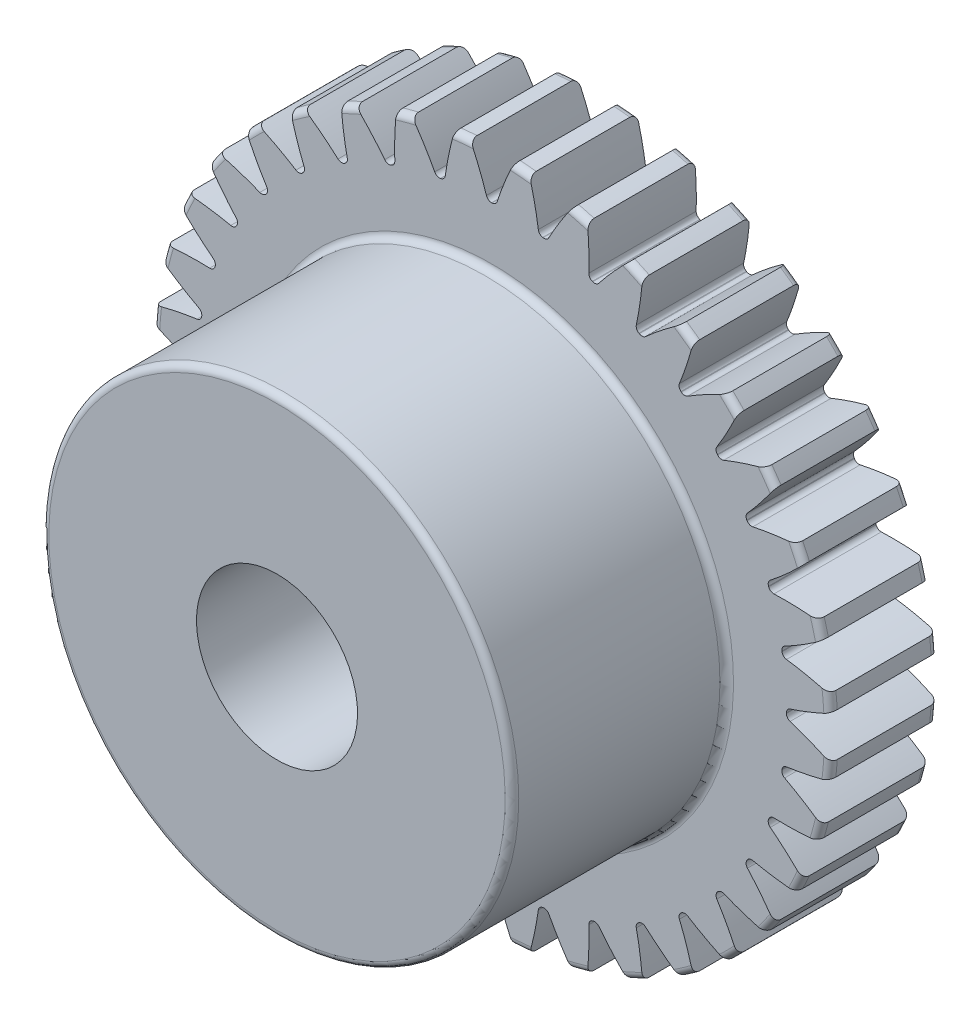
SolidWorks part; units mm, degrees
ref_plane "Front Plane" through (0, 0, 0) normal (0, 0, 1) x (1, 0, 0)
ref_plane "Top Plane" through (0, 0, 0) normal (0, 1, 0) x (1, 0, 0)
ref_plane "Right Plane" through (0, 0, 0) normal (1, 0, 0) x (0, 0, -1)
sketch "Sketch1" plane through (0, 0, 0) normal (0, 0, 1) x (1, 0, 0)
  line L0 (-457.2, 0) -> (457.2, 0) construction
  circle A0 centre (0, 0) radius 10.033 construction
  circle A1 centre (0, 0) radius 9.525 construction
  circle A2 centre (0, 0) radius 8.7101 construction
  circle A3 centre (0, 0) radius 6.9469 construction
  circle A4 centre (0, 0) radius 2.3813 construction
  dimension "D2" = 0.508
  dimension "D3" = 1.3229
  dimension "D1" = 1.3229
sketch "Sketch2" plane through (0, 0, 0) normal (1, 0, 0) x (0, 0, -1)
  line L0 (0, 0) -> (-3.175, 0) construction
  line L1 (-3.175, 0) -> (-9.525, 0) construction
  dimension "Overall Width" = 9.525
  dimension "Face Width" = 3.175
sketch "Sketch4" plane through (0, 0, 0) normal (1, 0, 0) x (0, 0, -1)
  line L0 (-9.525, 2.3813) -> (-9.525, 6.9469)
  line L1 (-9.525, 6.9469) -> (-3.175, 6.9469)
  line L2 (-3.175, 6.9469) -> (-3.175, 10.033)
  line L3 (-3.175, 10.033) -> (0, 10.033)
  line L4 (0, 10.033) -> (0, 2.3813)
  line L5 (-3.175, 6.9469) -> (-3.175, 0) construction
  line L6 (0, 10.033) -> (0, -10.033) construction
  line L7 (-3.175, 6.9469) -> (0, 6.9469) construction
  line L12 (-9.525, 2.3813) -> (0, 2.3813)
revolve "Revolve1" add sketch "Sketch4" angle 360 about L1
fillet "Fillet2" radius 0.2007 4 edges at (0, 6.9469, 9.525) (0, 6.9469, 3.175) (0, 10.033, 3.175) (0, 10.033, 0)
sketch "Sketch7" plane through (0, 0, 3.175) normal (0, 0, 1) x (1, 0, 0)
  line L0 (0, 0) -> (0, 10.033) construction
  line L1 (0.4155, 9.5159) -> (0.6217, 10.0137) construction
  line L3 (0.8744, 9.9948) -> (0.8302, 9.4888) construction
  line L4 (0.8302, 9.4888) -> (0.7591, 8.6769) construction
  line L5 (0, 0) -> (0.7591, 8.6769) construction
  line L6 (0.4155, 9.5159) -> (0, 0) construction
  line L7 (0.4155, 9.5159) -> (0.4376, 10.0235) construction
  line L8 (0.4155, 9.5159) -> (0, 0) construction
  circle A0 centre (0, 0) radius 10.033 construction
  arc A1 (-0.0073, 8.7101) -> (0.0073, 8.7101) centre (0, 0) cw
  circle A2 centre (0, 0) radius 8.7101 construction
  arc A3 (-0.4155, 9.5159) -> (0.4155, 9.5159) centre (0, 0) cw construction
  circle A4 centre (0, 0) radius 9.525 construction
  arc A5 (1.1103, 9.9714) -> (0.6381, 10.0127) centre (0, 0) ccw construction
  arc A6 (0.4155, 9.5159) -> (1.2433, 9.4435) centre (0, 0) cw construction
  arc A7 (-0.6381, 10.0127) -> (0.6381, 10.0127) centre (0, 0) cw
  arc A8 (0.1584, 8.8197) -> (0.6381, 10.0127) centre (9.2154, 5.8709) cw
  arc A9 (-0.1584, 8.8197) -> (-0.6381, 10.0127) centre (-9.2154, 5.8709) ccw
  arc A10 (-0.0073, 8.7101) -> (-0.1584, 8.8197) centre (-0.0074, 8.8688) cw
  arc A11 (0.0073, 8.7101) -> (0.1584, 8.8197) centre (0.0074, 8.8688) ccw
  point P26 (-0.1232, 8.7092)
  point P29 (0.1232, 8.7092)
  dimension "D4" = 0.1588
  dimension "D5" = 9.525
  dimension "D3" = 20
  dimension "D1" = 1.6624
  dimension "D2" = 0.8312
extrude "Cut-Extrude2" cut sketch "Sketch7" against normal through all
pattern_circular "CirPattern1" count 36 over 360 about axis through (0, 0, 0) along (0, 0, 1) of "Cut-Extrude2"
equation "\"D1@Sketch1\"=2.5*(\"Pitch Dia.@Sketch1\"/\"Number of Teeth@Sketch1\")"
equation "\"D1@CirPattern1\"=\"Number of Teeth@Sketch1\""
equation "\"D1@Fillet2\"=\"OD@Sketch1\"*.01"
equation "\"D1@Sketch7\"=3.14159*(\"Pitch Dia.@Sketch1\"/\"Number of Teeth@Sketch1\")"
equation "\"D2@Sketch7\"=\"D1@Sketch7\"/2"
equation "\"D4@Sketch7\"=\"D1@Sketch7\"*.0955"
equation "\"D5@Sketch7\"=\"Pitch Dia.@Sketch1\"/2"
